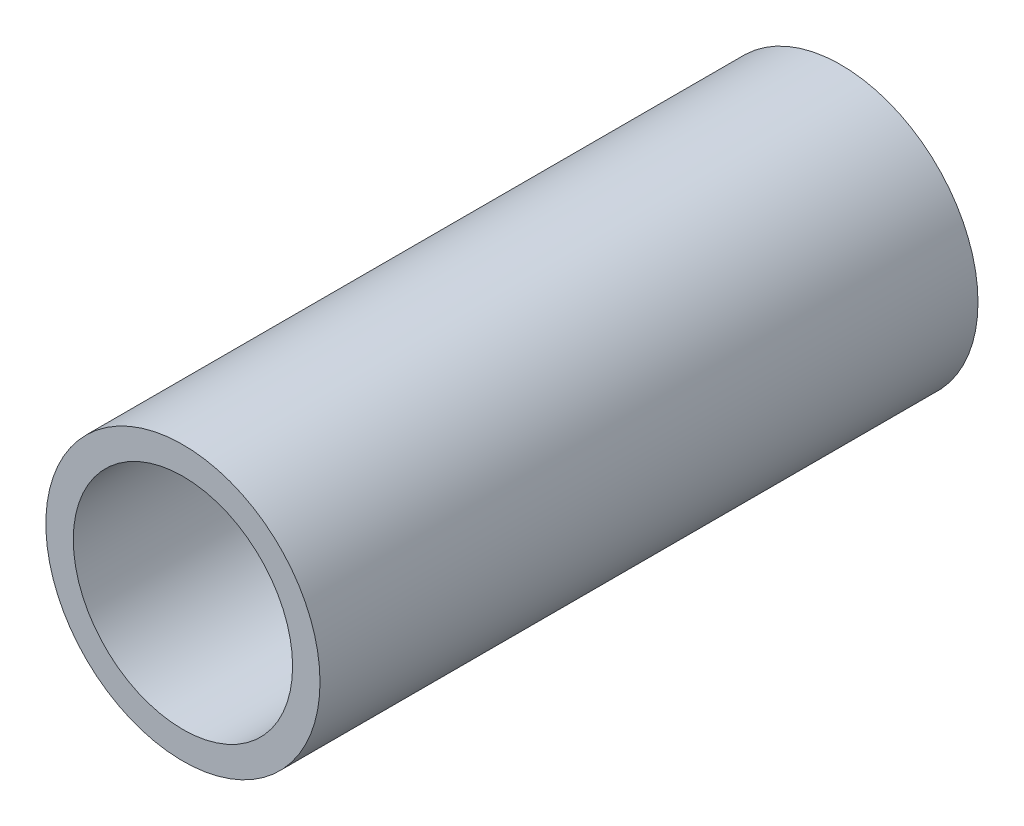
SolidWorks part; units mm, degrees
ref_plane "Přední rovina" through (0, 0, 0) normal (0, 0, 1) x (1, 0, 0)
ref_plane "Horní rovina" through (0, 0, 0) normal (0, 1, 0) x (1, 0, 0)
ref_plane "Pravá rovina" through (0, 0, 0) normal (1, 0, 0) x (0, 0, -1)
sketch "Skica1" plane through (0, 0, 0) normal (0, 0, 1) x (1, 0, 0)
  circle A0 centre (0, 0) radius 4
  circle A1 centre (0, 0) radius 5
  dimension "D1" = 8
  dimension "D2" = 10
extrude "Přidat vysunutím1" add sketch "Skica1" along normal blind 24
